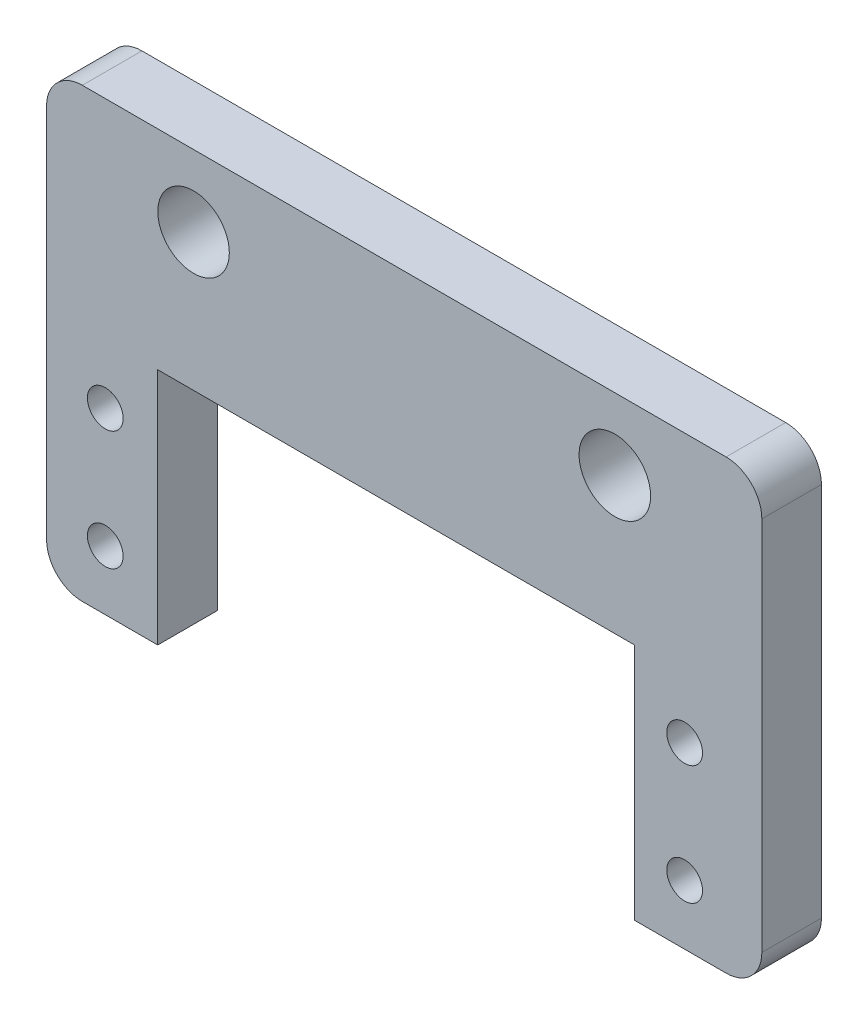
SolidWorks part; units mm, degrees
ref_plane "前视基准面" through (0, 0, 0) normal (0, 0, 1) x (1, 0, 0)
ref_plane "上视基准面" through (0, 0, 0) normal (0, 1, 0) x (1, 0, 0)
ref_plane "右视基准面" through (0, 0, 0) normal (1, 0, 0) x (0, 0, -1)
other "Configuration Table"
sketch "草图1" plane through (0, 0, 0) normal (0, 0, 1) x (1, 0, 0)
  line L0 (0, 0) -> (1.5, 0) construction
  line L2 (-15.5, 27.5) -> (38.5, 27.5)
  line L3 (-18.5, 24.5) -> (-18.5, -7)
  line L4 (-15.5, -10) -> (-9.175, -10)
  line L5 (41.5, 24.5) -> (41.5, -7)
  line L26 (30.825, 10) -> (-9.175, 10)
  line L27 (-9.175, 10) -> (-9.175, -10)
  line L28 (30.825, 10) -> (30.825, -10)
  line L29 (33.3, -10) -> (38.5, -10)
  line L30 (11.5, 18.5) -> (11.5, 10.6886) construction
  line L33 (26.375, 18.5) -> (2.3684, 18.5) construction
  line L34 (33.3, -10) -> (30.825, -10)
  circle A16 centre (-13.575, 5) radius 1.5
  circle A17 centre (-13.575, -5) radius 1.5
  circle A18 centre (35.025, 5) radius 1.5
  circle A19 centre (35.025, -5) radius 1.5
  arc A20 (38.5, 27.5) -> (41.5, 24.5) centre (38.5, 24.5) cw
  arc A21 (38.5, -10) -> (41.5, -7) centre (38.5, -7) ccw
  arc A22 (-18.5, -7) -> (-15.5, -10) centre (-15.5, -7) ccw
  arc A23 (-15.5, 27.5) -> (-18.5, 24.5) centre (-15.5, 24.5) ccw
  circle A32 centre (20.725, 0) radius 5.2518 construction
  point P14 (-6.71, 1.408)
  dimension "D2" = 3
  dimension "D3" = 3
  dimension "D4" = 60
  dimension "D6" = 3
  dimension "D8" = 14.3
  dimension "D9" = 14.3
  dimension "D10" = 5
  dimension "D11" = 14.875
  dimension "D12" = 10.1
  dimension "D5" = 3
  dimension "D13" = 3
  dimension "D15" = 10
  dimension "D17" = 34.3
  dimension "D18" = 5
  dimension "D7" = 37.5
  dimension "D14" = 10
  dimension "D16" = 34.3
  dimension "D19" = 40
extrude "凸台-拉伸1" add sketch "草图1" along normal blind 5
sketch "草图2" plane through (0, 0, 5) normal (0, 0, 1) x (1, 0, 0)
  line L0 (20.725, 0) -> (20.725, 6.3806) construction
  line L1 (-15.5, 27.5) -> (38.5, 27.5) construction
  line L2 (11.5, 27.5) -> (11.5, 21.5) construction
  line L5 (29.17, 21.5) -> (-6.17, 21.5) construction
  circle A2 centre (-6.17, 21.5) radius 3
  circle A3 centre (29.17, 21.5) radius 3
  dimension "D1" = 6
  dimension "D5" = 6
  dimension "D3" = 35.34
extrude "切除-拉伸1" cut sketch "草图2" against normal blind 10 contours A2 | A3
